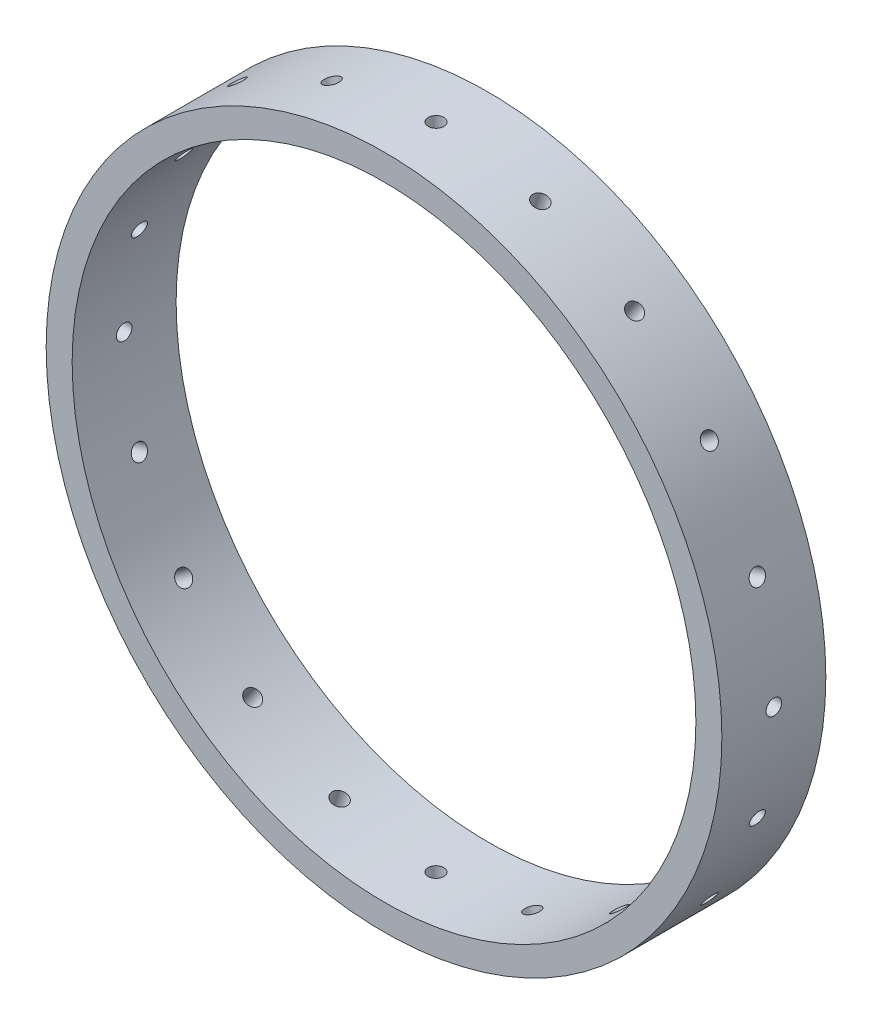
SolidWorks part; units mm, degrees
ref_plane "Front Plane" through (0, 0, 0) normal (0, 0, 1) x (1, 0, 0)
ref_plane "Top Plane" through (0, 0, 0) normal (0, 1, 0) x (1, 0, 0)
ref_plane "Right Plane" through (0, 0, 0) normal (1, 0, 0) x (0, 0, -1)
sketch "Sketch1" plane through (0, 0, 0) normal (0, 0, 1) x (1, 0, 0)
  circle A0 centre (0, 0) radius 65
  dimension "D1" = 130
extrude "Boss-Extrude1" add sketch "Sketch1" along normal mid plane 20
sketch "Sketch2" plane through (0, 0, 10) normal (0, 0, 1) x (1, 0, 0)
  circle A0 centre (0, 0) radius 60
  dimension "D1" = 120
extrude "Cut-Extrude1" cut sketch "Sketch2" against normal blind 20
ref_plane "Plane2" through (0, 65, 0) normal (0, 1, 0) x (1, 0, 0)
sketch "Sketch6" plane through (0, 65, 0) normal (0, 1, 0) x (1, 0, 0)
  circle A0 centre (0, 0) radius 1.5
  dimension "D1" = 3
extrude "Cut-Extrude2" cut sketch "Sketch6" against normal blind 20 contours A0
pattern_circular "CirPattern1" count 20 every 18 about axis through (0, 0, 10) along (0, 0, -1) of "Cut-Extrude2"
